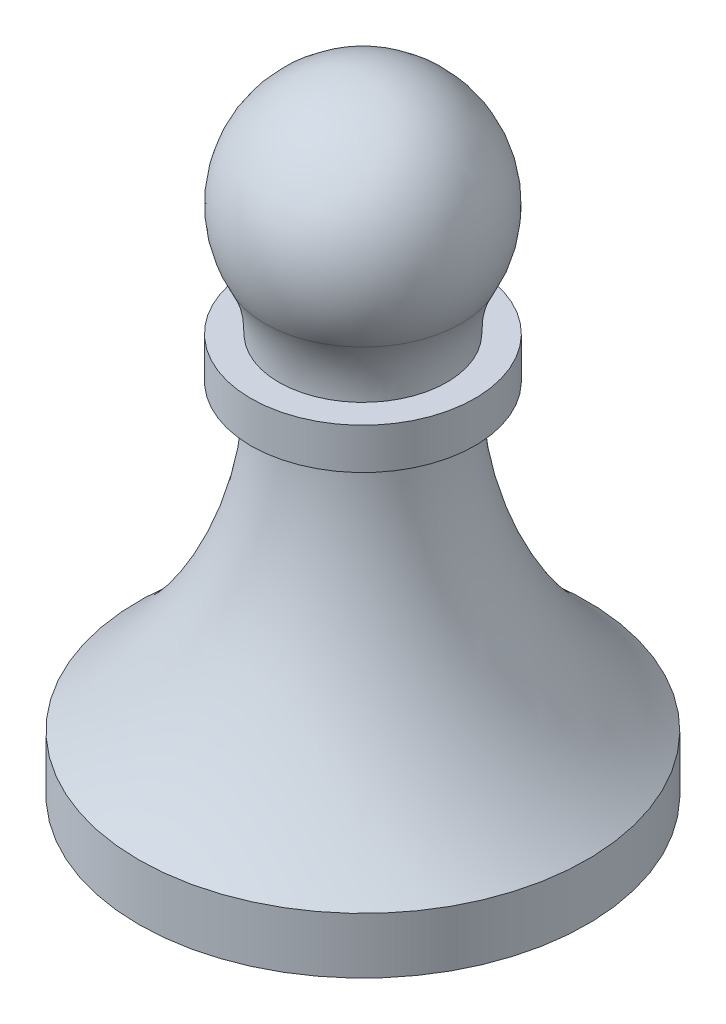
SolidWorks part; units mm, degrees
ref_plane "Front Plane" through (0, 0, 0) normal (0, 0, 1) x (1, 0, 0)
ref_plane "Top Plane" through (0, 0, 0) normal (0, 1, 0) x (1, 0, 0)
ref_plane "Right Plane" through (0, 0, 0) normal (1, 0, 0) x (0, 0, -1)
sketch "Sketch1" plane through (0, 0, 0) normal (0, 0, 1) x (1, 0, 0)
  line L0 (0, 36.3584) -> (0, -50.9193) construction
  line L1 (0, -27) -> (20, -27)
  line L2 (20, -27) -> (20, -32)
  line L3 (20, -32) -> (0, -32)
  line L4 (0, 0) -> (10, 0)
  line L5 (10, 0) -> (10, 3.6581)
  line L6 (10, 3.6581) -> (0, 3.6581)
  arc A0 (20, -27) -> (7.5, 0) centre (42.4995, -0.1901) cw
  arc A1 (8.7476, 8.8125) -> (0, 23.6581) centre (0, 13.6581) ccw
  arc A2 (8.7476, 8.8125) -> (7.5, 3.6581) centre (17.4952, 3.967) ccw
  point P9 (7.5, 3.6581)
  point P12 (7.5, 0)
  dimension "D7" = 35
  dimension "D8" = 20
  dimension "D9" = 10
  dimension "D1" = 27
  dimension "D2" = 20
  dimension "D3" = 5
  dimension "D4" = 10
  dimension "D5" = 7.5
  dimension "D6" = 7.5
revolve "Revolve2" add sketch "Sketch1" angle 360 about L0
scale "缩放比例1" scale about origin uniform scaling yes scale factor 0.6
